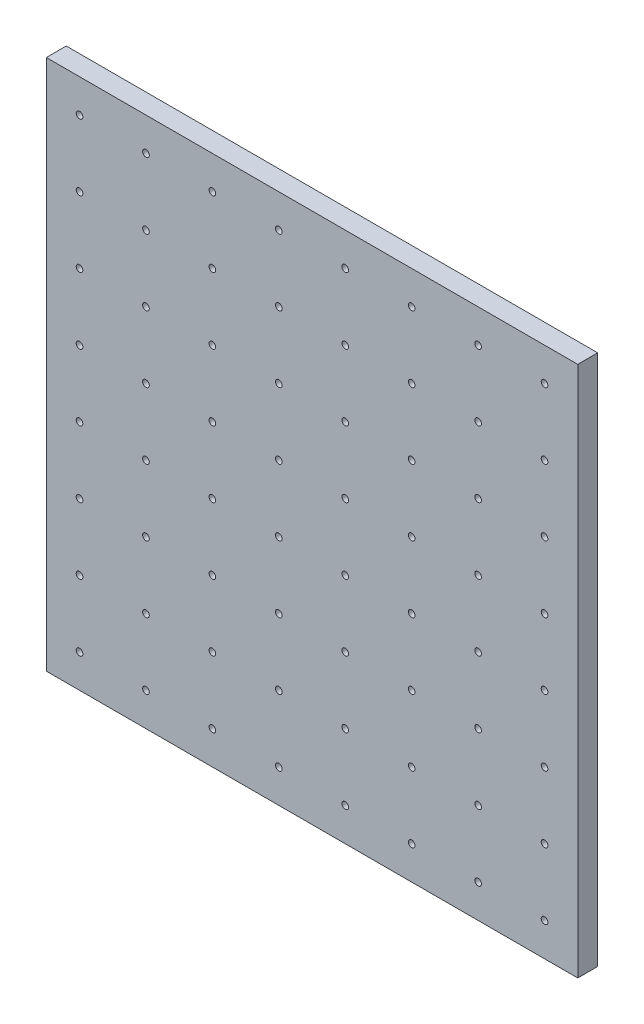
SolidWorks part; units mm, degrees
ref_plane "Front Plane" through (0, 0, 0) normal (0, 0, 1) x (1, 0, 0)
ref_plane "Top Plane" through (0, 0, 0) normal (0, 1, 0) x (1, 0, 0)
ref_plane "Right Plane" through (0, 0, 0) normal (1, 0, 0) x (0, 0, -1)
sketch "Sketch1" plane through (0, 0, 0) normal (0, 0, 1) x (1, 0, 0)
  line L1 (0, 0) -> (160, 0)
  line L2 (0, 0) -> (0, 160)
  line L3 (0, 160) -> (160, 160)
  line L4 (160, 0) -> (160, 160)
  dimension "D1" = 160
  dimension "D2" = 160
extrude "Boss-Extrude1" add sketch "Sketch1" along normal blind 7 contours L2 L1 L4 L3
sketch "Sketch2" plane through (0, 0, 7) normal (0, 0, 1) x (1, 0, 0)
  line L0 (0, 0) -> (0, 160) construction
  line L1 (0, 160) -> (160, 160) construction
  circle A0 centre (10, 150) radius 1
  circle A1 centre (30, 150) radius 1
  circle A2 centre (50, 150) radius 1
  circle A3 centre (70, 150) radius 1
  circle A4 centre (90, 150) radius 1
  circle A5 centre (110, 150) radius 1
  circle A6 centre (130, 150) radius 1
  circle A7 centre (150, 150) radius 1
  circle A8 centre (30, 130) radius 1
  circle A9 centre (10, 130) radius 1
  circle A10 centre (50, 130) radius 1
  circle A11 centre (70, 130) radius 1
  circle A12 centre (90, 130) radius 1
  circle A13 centre (110, 130) radius 1
  circle A14 centre (130, 130) radius 1
  circle A15 centre (150, 130) radius 1
  circle A16 centre (30, 110) radius 1
  circle A17 centre (10, 110) radius 1
  circle A18 centre (50, 110) radius 1
  circle A19 centre (70, 110) radius 1
  circle A20 centre (90, 110) radius 1
  circle A21 centre (110, 110) radius 1
  circle A22 centre (130, 110) radius 1
  circle A23 centre (150, 110) radius 1
  circle A24 centre (30, 90) radius 1
  circle A25 centre (10, 90) radius 1
  circle A26 centre (50, 90) radius 1
  circle A27 centre (70, 90) radius 1
  circle A28 centre (90, 90) radius 1
  circle A29 centre (110, 90) radius 1
  circle A30 centre (130, 90) radius 1
  circle A31 centre (150, 90) radius 1
  circle A32 centre (30, 70) radius 1
  circle A33 centre (10, 70) radius 1
  circle A34 centre (50, 70) radius 1
  circle A35 centre (70, 70) radius 1
  circle A36 centre (90, 70) radius 1
  circle A37 centre (110, 70) radius 1
  circle A38 centre (130, 70) radius 1
  circle A39 centre (150, 70) radius 1
  circle A40 centre (30, 50) radius 1
  circle A41 centre (10, 50) radius 1
  circle A42 centre (50, 50) radius 1
  circle A43 centre (70, 50) radius 1
  circle A44 centre (90, 50) radius 1
  circle A45 centre (110, 50) radius 1
  circle A46 centre (130, 50) radius 1
  circle A47 centre (150, 50) radius 1
  circle A48 centre (30, 30) radius 1
  circle A49 centre (10, 30) radius 1
  circle A50 centre (50, 30) radius 1
  circle A51 centre (70, 30) radius 1
  circle A52 centre (90, 30) radius 1
  circle A53 centre (110, 30) radius 1
  circle A54 centre (130, 30) radius 1
  circle A55 centre (150, 30) radius 1
  circle A56 centre (30, 10) radius 1
  circle A57 centre (10, 10) radius 1
  circle A58 centre (50, 10) radius 1
  circle A59 centre (70, 10) radius 1
  circle A60 centre (90, 10) radius 1
  circle A61 centre (110, 10) radius 1
  circle A62 centre (130, 10) radius 1
  circle A63 centre (150, 10) radius 1
  dimension "D1" = 10
  dimension "D3" = 2
  dimension "D2" = 10
  dimension "D4" = 8
  dimension "D5" = 8
extrude "Cut-Extrude1" cut sketch "Sketch2" against normal blind 3
sketch "Sketch5" plane through (0, 0, 7) normal (0, 0, 1) x (1, 0, 0)
  line L0 (0, 160) -> (160, 160)
sketch "Sketch7" plane through (0, 0, 0) normal (-1, 0, 0) x (0, 0, 1)
  line L0 (7, 0) -> (0, 0) construction
  line L1 (0, 160) -> (1, 160)
  line L2 (0, 160) -> (0, 0)
  line L3 (0, 0) -> (1, 0)
  line L4 (1, 160) -> (1, 0)
  dimension "D1" = 1
extrude "Cut-Extrude2" cut sketch "Sketch7" against normal blind 300
